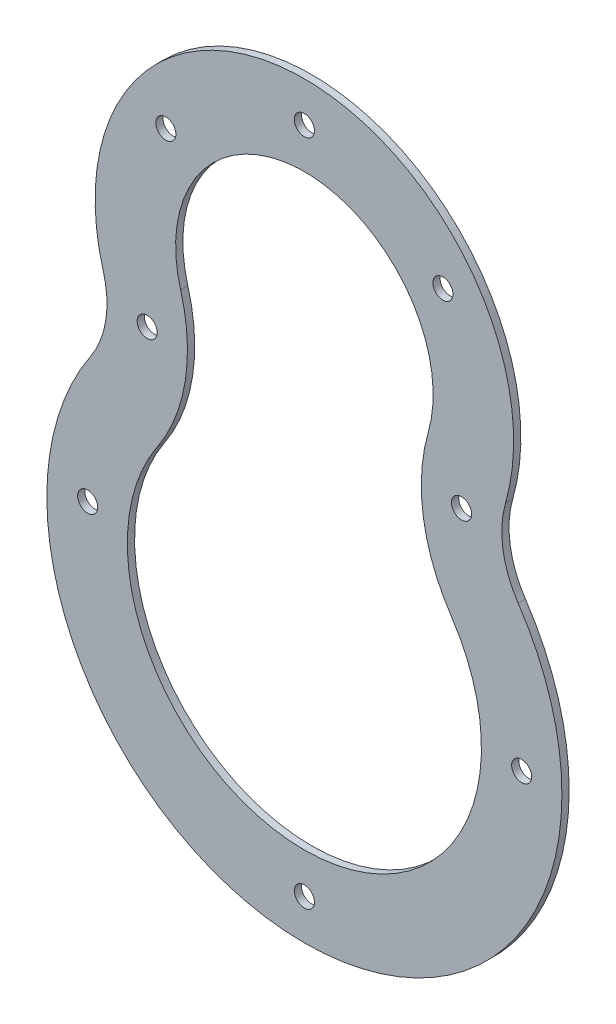
SolidWorks part; units mm, degrees
ref_plane "Front Plane" through (0, 0, 0) normal (0, 0, 1) x (1, 0, 0)
ref_plane "Top Plane" through (0, 0, 0) normal (0, 1, 0) x (1, 0, 0)
ref_plane "Right Plane" through (0, 0, 0) normal (1, 0, 0) x (0, 0, -1)
sketch "Sketch1" plane through (0, 0, 0) normal (0, 0, 1) x (1, 0, 0)
  line L0 (0, 35) -> (0, 0) construction
  circle A0 centre (0, 0) radius 32 construction
  circle A1 centre (0, 35) radius 26 construction
  arc A2 (-24.9934, 27.8353) -> (-26.5664, 17.839) centre (-36.5287, 24.5286) cw
  arc A3 (24.9934, 27.8353) -> (26.5664, 17.839) centre (36.5287, 24.5286) ccw
  arc A4 (-24.9934, 27.8353) -> (24.9934, 27.8353) centre (0, 35) cw
  arc A5 (-26.5664, 17.839) -> (26.5664, 17.839) centre (0, 0) ccw
  arc A6 (-15.3805, 30.591) -> (15.3805, 30.591) centre (0, 35) cw
  arc A7 (15.3805, 30.591) -> (18.2644, 12.2643) centre (36.5287, 24.5286) ccw
  arc A8 (-18.2644, 12.2643) -> (18.2644, 12.2643) centre (0, 0) ccw
  arc A9 (-15.3805, 30.591) -> (-18.2644, 12.2643) centre (-36.5287, 24.5286) cw
  arc A10 (-20.1869, 29.2132) -> (20.1869, 29.2132) centre (0, 35) cw construction
  arc A11 (20.1869, 29.2132) -> (22.4154, 15.0516) centre (36.5287, 24.5286) ccw construction
  arc A12 (-22.4154, 15.0516) -> (22.4154, 15.0516) centre (0, 0) ccw construction
  arc A13 (-20.1869, 29.2132) -> (-22.4154, 15.0516) centre (-36.5287, 24.5286) cw construction
  point P29 (-26.9237, 2.0286)
  point P30 (-19.5287, 24.5286)
  point P31 (17.2138, 47.0286)
  point P32 (-17.2138, 47.0286)
  point P33 (0, 56)
  point P34 (19.5287, 24.5286)
  point P35 (27, 0)
  point P36 (0, 0)
  point P37 (19.7354, 21.886)
  point P38 (0, 0)
  point P39 (0, 0)
  dimension "D2" = 64
  dimension "D3" = 52
  dimension "D4" = 12
  dimension "D5" = 16
  dimension "D6" = 21
  dimension "D1" = 35
  dimension "D7" = 22.5
  dimension "D8" = 45
extrude "Boss-Extrude1" add sketch "Sketch1" along normal blind 0.9
hole_wizard "M3 Tapped Hole1" positions "Sketch4" profile "Sketch5" tap size "M3" standard "ISO" end condition through all
sketch "Sketch4" plane through (0, 0, 0.9) normal (0, 0, 1) x (1, 0, 0)
  arc A0 (20.1869, 29.2132) -> (-20.1869, 29.2132) centre (0, 35) ccw construction
  arc A1 (-22.4154, 15.0516) -> (22.4154, 15.0516) centre (0, 0) ccw construction
  point P0 (27, 0)
  point P3 (19.5287, 24.5286)
  point P6 (-19.5287, 24.5286)
  point P9 (-26.9237, 2.0286)
  point P12 (0, 56)
  point P17 (17.2138, 47.0286)
  point P20 (-17.2138, 47.0286)
  point P23 (0, -27)
sketch "Sketch5" plane through (27, 0, 0.9) normal (1, 0, 0) x (0, -1, 0)
  line L0 (0, 0) -> (0, 0.9)
  line L1 (0, 0.9) -> (1.25, 0.9)
  line L2 (1.25, 0.9) -> (1.25, 0)
  line L5 (1.25, 0) -> (0, 0)
  line L11 (0, -6.35) -> (0, 107.95) construction
  dimension "Thru Tap Drill Dia." = 2.5
  dimension "Thru Tap Drill Depth" = 0.9
cosmetic thread "Hole Thread1" parameters "D2"=3
cosmetic thread "Hole Thread2" parameters "D2"=3
cosmetic thread "Hole Thread3" parameters "D2"=3
cosmetic thread "Hole Thread4" parameters "D2"=3
cosmetic thread "Hole Thread5" parameters "D2"=3
cosmetic thread "Hole Thread6" parameters "D2"=3
cosmetic thread "Hole Thread7" parameters "D2"=3
cosmetic thread "Hole Thread8" parameters "D2"=3
